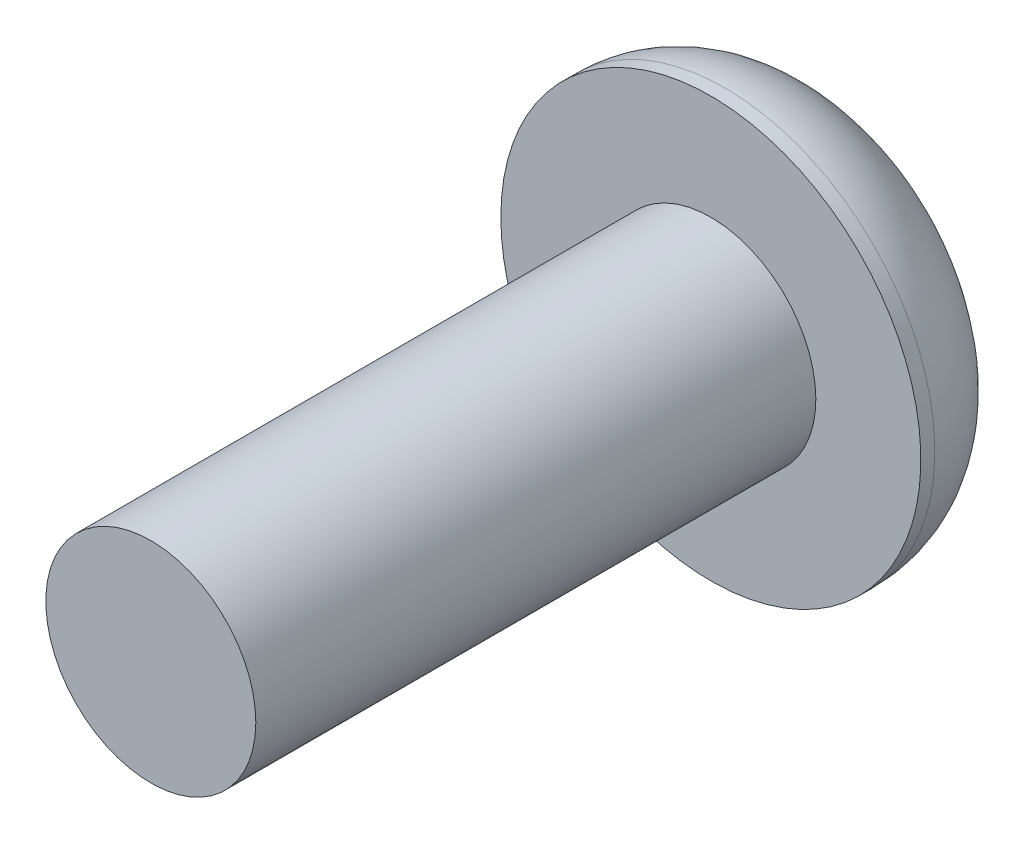
SolidWorks part; units mm, degrees
ref_plane "前视基准面" through (0, 0, 0) normal (0, 0, 1) x (1, 0, 0)
ref_plane "上视基准面" through (0, 0, 0) normal (0, 1, 0) x (1, 0, 0)
ref_plane "右视基准面" through (0, 0, 0) normal (1, 0, 0) x (0, 0, -1)
sketch "草图1" plane through (0, 0, 0) normal (0, 0, 1) x (1, 0, 0)
  circle A0 centre (0, 0) radius 1.5
extrude "凸台-拉伸1" add sketch "草图1" along normal blind 8
sketch "草图2" plane through (0, 0, 0) normal (0, 0, -1) x (-1, 0, 0)
  circle A0 centre (0, 0) radius 3
extrude "凸台-拉伸2" add sketch "草图2" along normal blind 1.7
fillet "圆角1" radius 1.5 1 edges at (-3, 0, -1.7)
thread "螺纹线1" pitch 1.27 start angle 0, offset 0, length 0, pitch 1.27, diameter 3
ref_plane "基准面1" through (1.5, 0, 0) normal (0, -1, 0) x (1, 0, 0)
sketch "螺纹线轮廓1" plane through (1.5, 0, 0) normal (0, -1, 0) x (1, 0, 0)
  line L0 (0, 0) -> (0, 1.27) construction
  line L11 (0, 0) -> (0, 1.1112)
  line L12 (0, 1.1112) -> (-0.6874, 0.7144)
  line L13 (-0.6874, 0.7144) -> (-0.6874, 0.3969)
  line L15 (-0.6874, 0.3969) -> (0, 0)
  line L17 (-0.6874, 0.5556) -> (0, 0.5556) construction
  point P2 (0, 0)
  dimension "Pitch" = 1.27
  dimension "Profile_Angle" = 60
  dimension "Profile_Land" = 0.3175
  dimension "Profile_Height" = 0.6874
